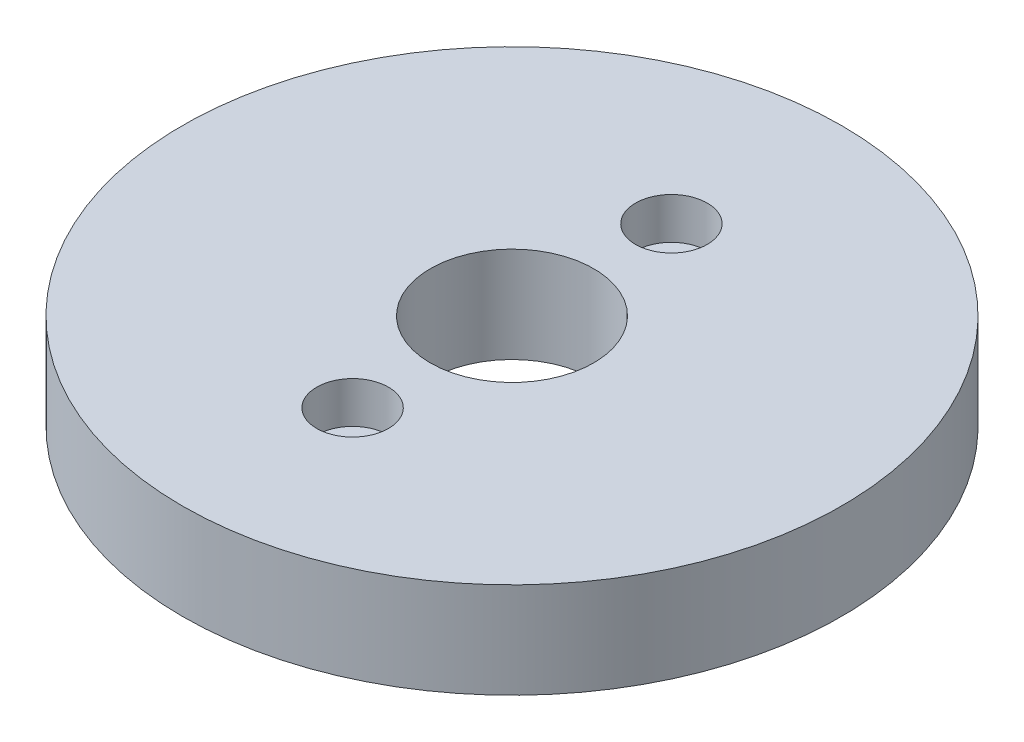
SolidWorks part; units mm, degrees
ref_plane "Front Plane" through (0, 0, 0) normal (0, 0, 1) x (1, 0, 0)
ref_plane "Top Plane" through (0, 0, 0) normal (0, 1, 0) x (1, 0, 0)
ref_plane "Right Plane" through (0, 0, 0) normal (1, 0, 0) x (0, 0, -1)
sketch "Sketch1" plane through (0, 0, 0) normal (0, 1, 0) x (1, 0, 0)
  circle A0 centre (0, 0) radius 41.35
extrude "Boss-Extrude1" add sketch "Sketch1" along normal blind 12
sketch "Sketch2" plane through (0, 12, 0) normal (0, 1, 0) x (1, 0, 0)
  circle A0 centre (0, 20) radius 2.75
  circle A1 centre (0, -20) radius 2.75
  dimension "D1" = 20
  dimension "D2" = 20
extrude "Cut-Extrude1" cut sketch "Sketch2" against normal blind 25
sketch "Sketch3" plane through (0, 12, 0) normal (0, 1, 0) x (1, 0, 0)
  circle A1 centre (0, 20) radius 4.5
  circle A2 centre (0, -20) radius 4.5
sketch "Sketch4" plane through (0, 12, 0) normal (0, 1, 0) x (1, 0, 0)
  circle A0 centre (0, 0) radius 10.25
extrude "Cut-Extrude2" cut sketch "Sketch4" against normal blind 25
extrude "Cut-Extrude3" cut sketch "Sketch3" against normal blind 5.2
